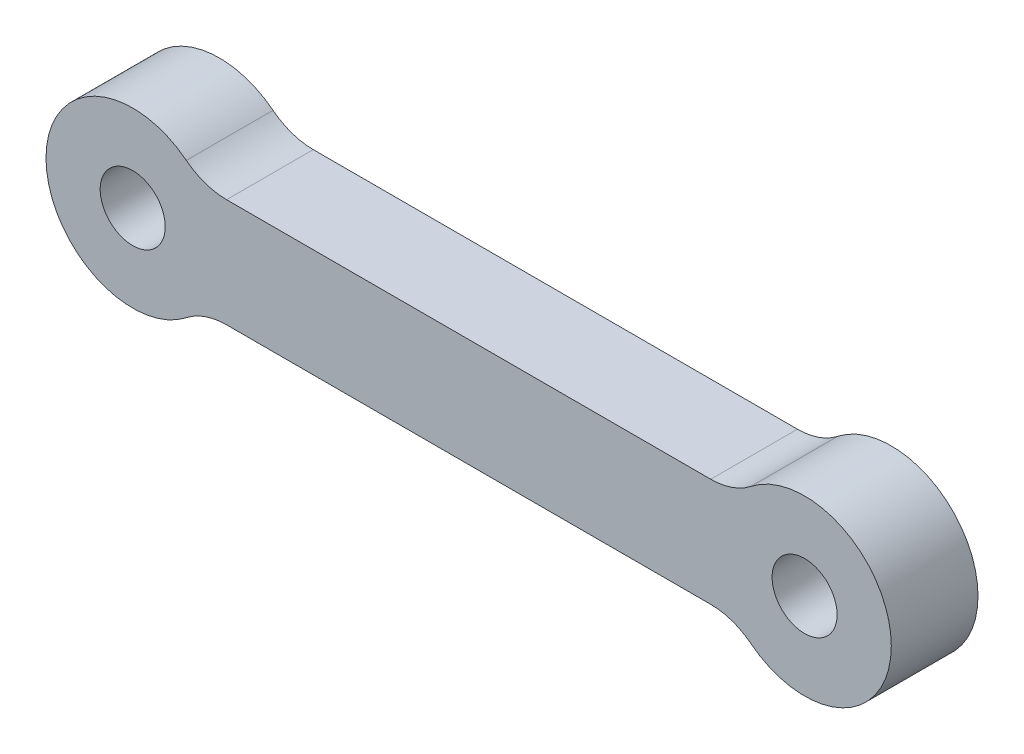
SolidWorks part; units mm, degrees
ref_plane "Front Plane" through (0, 0, 0) normal (0, 0, 1) x (1, 0, 0)
ref_plane "Top Plane" through (0, 0, 0) normal (0, 1, 0) x (1, 0, 0)
ref_plane "Right Plane" through (0, 0, 0) normal (1, 0, 0) x (0, 0, -1)
sketch "Sketch2" plane through (0, 0, 0) normal (0, 0, 1) x (1, 0, 0)
  line L2 (12.4874, 0.8374) -> (-12.2676, 0.8374)
  line L4 (12.4874, -4.1626) -> (-12.2676, -4.1626)
  arc A0 (-12.2676, 0.8374) -> (-12.2676, -4.1626) centre (-15.3901, -1.6626) ccw
  circle A1 centre (-15.3901, -1.6626) radius 1.5
  arc A2 (12.4874, 0.8374) -> (12.4874, -4.1626) centre (15.6099, -1.6626) cw
  circle A3 centre (15.6099, -1.6626) radius 1.5
  point P3 (0, 0)
  point P4 (0, 0)
  dimension "D2" = 8
  dimension "D3" = 3
  dimension "D5" = 3
  dimension "D1" = 31
  dimension "D4" = 5
sketch "Sketch4" plane through (0, 0, 0) normal (0, 0, 1) x (1, 0, 0)
  line L0 (12.4874, 0.8374) -> (-12.2676, 0.8374) construction
  line L1 (12.4874, 0.8374) -> (-12.2676, 0.8374)
  line L2 (12.4874, -4.1626) -> (-12.2676, -4.1626) construction
  line L3 (12.4874, -4.1626) -> (-12.2676, -4.1626)
  circle A0 centre (15.6099, -1.6626) radius 1.5 construction
  arc A1 (12.4874, -4.1626) -> (12.4874, 0.8374) centre (15.6099, -1.6626) ccw construction
  circle A2 centre (-15.3901, -1.6626) radius 1.5 construction
  arc A3 (-12.2676, 0.8374) -> (-12.2676, -4.1626) centre (-15.3901, -1.6626) ccw construction
  circle A4 centre (15.6099, -1.6626) radius 1.5
  arc A5 (12.4874, -4.1626) -> (12.4874, 0.8374) centre (15.6099, -1.6626) ccw
  circle A6 centre (-15.3901, -1.6626) radius 1.5
  arc A7 (-12.2676, 0.8374) -> (-12.2676, -4.1626) centre (-15.3901, -1.6626) ccw
sketch "Sketch5" plane through (0, 0, 0) normal (0, 0, 1) x (1, 0, 0)
  line L2 (12.4874, 0.8374) -> (-12.2676, 0.8374)
  line L3 (-12.2676, -4.1626) -> (12.4874, -4.1626)
  line L4 (11.2798, 0.8374) -> (-11.0599, 0.8374)
  line L5 (-11.0599, -4.1626) -> (11.2798, -4.1626)
  arc A0 (11.2798, 0.8374) -> (13.1356, 1.4803) centre (11.2798, 3.8374) ccw
  circle A1 centre (-15.3901, -1.6626) radius 1.5
  circle A2 centre (-15.3901, -1.6626) radius 1.5
  circle A3 centre (15.6099, -1.6626) radius 1.5
  circle A4 centre (15.6099, -1.6626) radius 1.5
  arc A5 (11.2798, -4.1626) -> (13.1356, -4.8054) centre (11.2798, -7.1626) cw
  arc A6 (-12.2676, 0.8374) -> (-12.2676, -4.1626) centre (-15.3901, -1.6626) ccw
  arc A7 (12.4874, -4.1626) -> (12.4874, 0.8374) centre (15.6099, -1.6626) ccw
  arc A8 (-12.9157, 1.4803) -> (-12.9157, -4.8054) centre (-15.3901, -1.6626) ccw
  arc A9 (13.1356, -4.8054) -> (13.1356, 1.4803) centre (15.6099, -1.6626) ccw
  arc A10 (-12.9157, -4.8054) -> (-11.0599, -4.1626) centre (-11.0599, -7.1626) cw
  arc A11 (-11.0599, 0.8374) -> (-12.9157, 1.4803) centre (-11.0599, 3.8374) cw
  dimension "D4" = 3
  dimension "D1" = 0
  dimension "D2" = 0
  dimension "D3" = 0
extrude "Boss-Extrude1" add sketch "Sketch5" along normal blind 4
